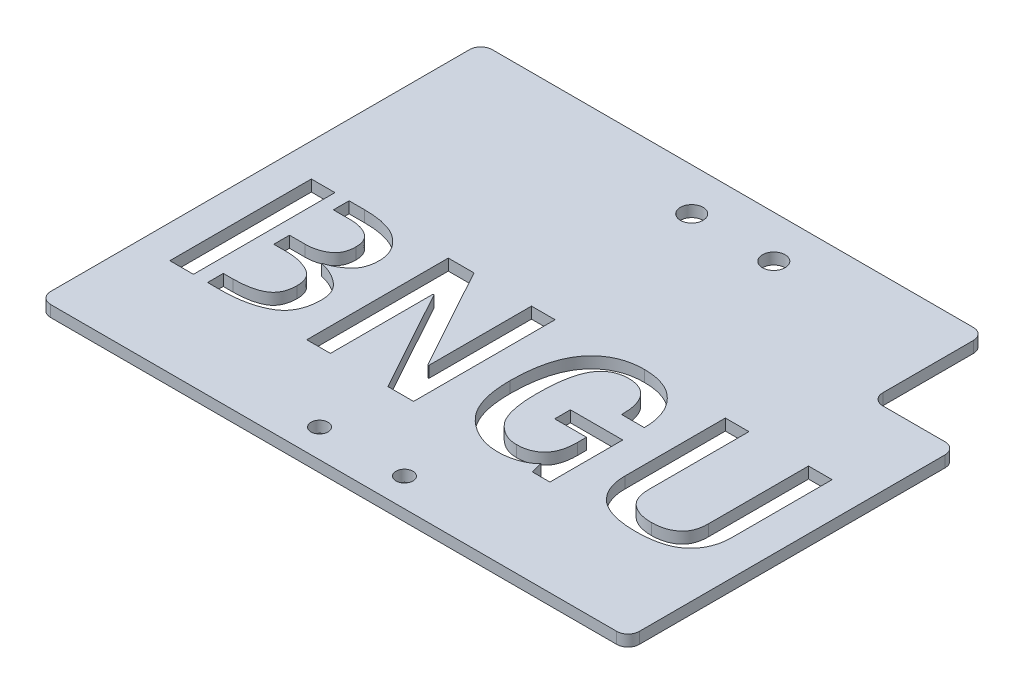
SolidWorks part; units mm, degrees
ref_plane "前视基准面" through (0, 0, 0) normal (0, 0, 1) x (1, 0, 0)
ref_plane "上视基准面" through (0, 0, 0) normal (0, 1, 0) x (1, 0, 0)
ref_plane "右视基准面" through (0, 0, 0) normal (1, 0, 0) x (0, 0, -1)
other "Configuration Table"
sketch "草图1" plane through (0, 0, 0) normal (0, 1, 0) x (1, 0, 0)
  line L0 (0, 0) -> (0, 78)
  line L1 (0, 78) -> (89, 78)
  line L2 (89, 78) -> (89, 58)
  line L3 (89, 58) -> (104, 58)
  line L4 (104, 58) -> (104, 0)
  line L5 (104, 0) -> (0, 0)
  dimension "D1" = 104
  dimension "D2" = 15
  dimension "D3" = 20
  dimension "D4" = 78
extrude "凸台-拉伸1" add sketch "草图1" along normal blind 2
fillet "圆角1" radius 2 6 edges at (0, 1, 0) (0, 1, -78) (89, 1, -78) (89, 1, -58) (104, 1, -58) (104, 1, 0)
sketch "草图2" plane through (0, 2, 0) normal (0, 1, 0) x (1, 0, 0)
  line L0 (104, 29) -> (0, 29) construction
  line L1 (104, 2) -> (104, 56) construction
  line L2 (0, 76) -> (0, 2) construction
  line L3 (0, 16.5) -> (104, 16.5) construction
  text T0 "BNGU" font "黑体" height 25
  dimension "D1" = 12.5
extrude "logo" cut sketch "草图2" against normal blind 2
sketch "草图3" plane through (0, 2, 0) normal (0, 1, 0) x (1, 0, 0)
  line L12 (5.8196, 42.231) -> (15.2521, 42.231) construction
  line L13 (9.989, 42.231) -> (12.489, 42.231)
  line L18 (9.989, 42.231) -> (9.989, 17.231)
  line L19 (9.989, 17.231) -> (12.489, 17.231)
  line L20 (12.489, 42.231) -> (12.489, 17.231)
  line L21 (14.8893, 17.231) -> (5.8196, 17.231) construction
  line L22 (9.989, 28.9269) -> (9.989, 20.0088) construction
  dimension "D1" = 2.5
extrude "凸台-拉伸2" add sketch "草图3" against normal blind 2
sketch "草图4" plane through (0, 2, 0) normal (0, 1, 0) x (1, 0, 0)
  line L0 (44.75, 70.5) -> (59.25, 70.5) construction
  line L1 (52, 70.5) -> (52, 0) construction
  line L2 (2, 0) -> (102, 0) construction
  line L3 (87, 78) -> (2, 78) construction
  line L4 (44.5, 5) -> (59.5, 5) construction
  circle A0 centre (44.75, 70.5) radius 2
  circle A1 centre (59.25, 70.5) radius 2
  circle A2 centre (44.5, 5) radius 1.5
  circle A3 centre (59.5, 5) radius 1.5
  point P14 (52, 5)
  dimension "D3" = 4
  dimension "D5" = 3
  dimension "D1" = 14.5
  dimension "D2" = 7.5
  dimension "D4" = 15
  dimension "D6" = 5
extrude "切除-拉伸3" cut sketch "草图4" against normal blind 2
